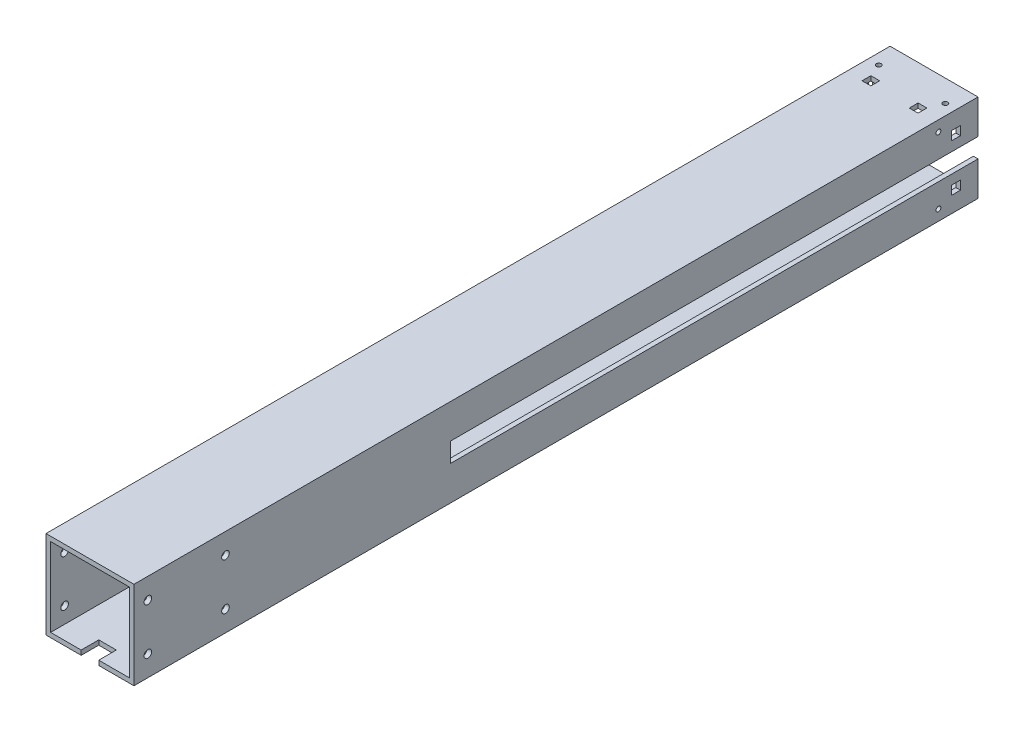
SolidWorks part; units mm, degrees
ref_plane "Front Plane" through (0, 0, 0) normal (1, 0, 0) x (0, 1, 0)
ref_plane "Top Plane" through (0, 0, 0) normal (0, 0, 1) x (0, 1, 0)
ref_plane "Right Plane" through (0, 0, 0) normal (0, 1, 0) x (-1, 0, 0)
sketch "Sketch1" plane through (0, 0, 0) normal (0, 0, 1) x (0, 1, 0)
  line L0 (28.4162, -28.4162) -> (28.4162, 28.4162)
  line L1 (31.75, -31.75) -> (-31.75, -31.75)
  line L2 (31.75, -31.75) -> (31.75, 31.75)
  line L3 (31.75, 31.75) -> (-31.75, 31.75)
  line L4 (-31.75, -31.75) -> (-31.75, 31.75)
  line L5 (31.75, -31.75) -> (-31.75, 31.75) construction
  line L6 (31.75, 31.75) -> (-31.75, -31.75) construction
  line L7 (28.4162, 28.4162) -> (-28.4162, 28.4162)
  line L8 (-28.4162, -28.4162) -> (-28.4162, 28.4162)
  line L9 (28.4162, -28.4162) -> (-28.4162, -28.4162)
  line L11 (6.985, -31.75) -> (-6.985, -31.75)
  line L12 (6.985, -31.75) -> (6.985, -28.4163)
  line L13 (6.985, -28.4163) -> (-6.985, -28.4163)
  line L14 (-6.985, -31.75) -> (-6.985, -28.4163)
  line L15 (6.985, -31.75) -> (-6.985, -28.4163) construction
  line L16 (6.985, -28.4163) -> (-6.985, -31.75) construction
  point P0 (0, 0)
  point P10 (0, -30.0831)
  dimension "D1" = 63.5
  dimension "D3" = 13.97
  dimension "D2" = 56.8325
extrude "Boss-Extrude1" add sketch "Sketch1" along normal blind 609.6 contours L1 L14 L9 L8 L7 L0 L12 L2 L3 L4
sketch "Sketch2" plane through (0, 0, 0) normal (0, 1, 0) x (-1, 0, 0)
  line L0 (-28.4162, 0) -> (28.4162, 0) construction
  line L1 (-28.4162, 0) -> (28.4162, 0) construction
  line L2 (0, 0) -> (0, 609.6) construction
  line L3 (-31.75, 609.6) -> (31.75, 609.6) construction
  line L5 (22.225, 6.35) -> (-22.225, 6.35) construction
  line L6 (22.225, 6.35) -> (22.225, 19.05) construction
  line L7 (22.225, 19.05) -> (-22.225, 19.05) construction
  line L8 (-22.225, 6.35) -> (-22.225, 19.05) construction
  line L9 (22.225, 6.35) -> (-22.225, 19.05) construction
  line L10 (22.225, 19.05) -> (-22.225, 6.35) construction
  circle A3 centre (-22.225, 19.05) radius 1.75 construction
  circle A4 centre (22.225, 19.05) radius 1.75 construction
  circle A5 centre (22.225, 6.35) radius 1.75 construction
  circle A6 centre (-22.225, 6.35) radius 1.75 construction
  circle A7 centre (-24.05, 15.875) radius 1.75
  circle A8 centre (24.05, 15.875) radius 1.75
  point P2 (0, 12.7)
  dimension "D1" = 3.5
  dimension "D2" = 6.35
  dimension "D6" = 15.875
  dimension "D3" = 12.7
  dimension "D4" = 44.45
  dimension "D5" = 24.05
extrude "Cut-Extrude1" cut sketch "Sketch2" against normal blind 254 and the other way blind 254
sketch "Sketch4" plane through (31.75, 0, 0) normal (1, 0, 0) x (0, 1, 0)
  line L0 (-28.4162, 609.6) -> (-28.4162, 0) construction
  line L1 (-28.4162, 609.6) -> (-28.4162, 0) construction
  line L2 (-6.985, 0) -> (-31.75, 0) construction
  line L3 (0, 0) -> (0, 609.6) construction
  line L4 (-6.985, 609.6) -> (-31.75, 609.6) construction
  line L5 (31.75, 0) -> (6.985, 0) construction
  circle A1 centre (-22.225, 25.4) radius 1.75 construction
  circle A3 centre (-12.7, 12.7) radius 1.75 construction
  circle A6 centre (12.7, 12.7) radius 1.75 construction
  circle A7 centre (22.225, 25.4) radius 1.75 construction
  circle A8 centre (24.05, 28.575) radius 1.75
  circle A9 centre (-24.05, 28.575) radius 1.75
  dimension "D1" = 22.225
  dimension "D2" = 3.5
  dimension "D4" = 12.7
  dimension "D6" = 24.05
  dimension "D7" = 3.5
  dimension "D3" = 25.4
  dimension "D5" = 12.7
  dimension "D8" = 28.575
extrude "Cut-Extrude2" cut sketch "Sketch4" against normal blind 254
sketch "Sketch6" plane through (31.75, 0, 0) normal (1, 0, 0) x (0, 1, 0)
  line L0 (31.75, 14.125) -> (31.75, 17.625) construction
  line L5 (31.75, 14.125) -> (31.75, 17.625) construction
  line L6 (0, 0) -> (0, 19.05) construction
  line L7 (15.05, 20.875) -> (19.05, 20.875) construction
  line L8 (15.05, 20.875) -> (15.05, 10.875) construction
  line L9 (15.05, 10.875) -> (19.05, 10.875) construction
  line L10 (19.05, 20.875) -> (19.05, 10.875) construction
  line L11 (13.875, 19.05) -> (20.225, 19.05)
  line L12 (13.875, 19.05) -> (13.875, 12.7)
  line L13 (13.875, 12.7) -> (20.225, 12.7)
  line L14 (20.225, 19.05) -> (20.225, 12.7)
  line L15 (28.4163, 0) -> (-28.4162, 0) construction
  line L16 (-13.875, 12.7) -> (-20.225, 12.7)
  line L17 (-20.225, 19.05) -> (-20.225, 12.7)
  line L18 (-13.875, 19.05) -> (-20.225, 19.05)
  line L19 (-13.875, 19.05) -> (-13.875, 12.7)
  point P3 (0, 0)
  point P7 (31.75, 15.875)
  point P9 (19.05, 15.875)
  point P11 (17.05, 20.875)
  point P12 (20.225, 15.875)
  point P17 (17.05, 19.05)
  dimension "D1" = 10
  dimension "D2" = 4
  dimension "D3" = 19.05
  dimension "D4" = 6.35
  dimension "D5" = 6.35
extrude "Cut-Extrude4" cut sketch "Sketch6" against normal blind 90.678
sketch "Sketch7" plane through (0, 31.75, 0) normal (0, 1, 0) x (-1, 0, 0)
  line L0 (-31.75, 30.325) -> (-31.75, 26.825) construction
  line L1 (-31.75, 30.325) -> (-31.75, 26.825)
  line L2 (0, 0) -> (0, 31.75) construction
  line L3 (-19.05, 33.575) -> (-15.05, 33.575) construction
  line L4 (-19.05, 33.575) -> (-19.05, 23.575) construction
  line L5 (-19.05, 23.575) -> (-15.05, 23.575) construction
  line L6 (-15.05, 33.575) -> (-15.05, 23.575) construction
  line L7 (-20.225, 31.75) -> (-13.875, 31.75)
  line L8 (-20.225, 31.75) -> (-20.225, 25.4)
  line L9 (-20.225, 25.4) -> (-13.875, 25.4)
  line L10 (-13.875, 31.75) -> (-13.875, 25.4)
  line L11 (-31.75, 0) -> (31.75, 0) construction
  line L12 (20.225, 25.4) -> (13.875, 25.4)
  line L13 (13.875, 31.75) -> (13.875, 25.4)
  line L14 (20.225, 31.75) -> (13.875, 31.75)
  line L15 (20.225, 31.75) -> (20.225, 25.4)
  point P6 (-31.75, 28.575)
  point P7 (-19.05, 28.575)
  point P10 (-17.05, 33.575)
  point P14 (-20.225, 28.575)
  point P15 (-17.05, 31.75)
  dimension "D1" = 10
  dimension "D2" = 4
  dimension "D3" = 19.05
  dimension "D4" = 6.35
extrude "Cut-Extrude5" cut sketch "Sketch7" against normal blind 122.174 contours L10 L7 L8 L9 | L15 L14 L13 L12
sketch "Sketch8" plane through (31.75, 0, 0) normal (1, 0, 0) x (0, 1, 0)
  line L0 (31.75, 609.6) -> (31.75, 0) construction
  line L1 (-31.75, 609.6) -> (31.75, 609.6)
  line L2 (-31.75, 609.6) -> (-31.75, 381)
  line L3 (-31.75, 381) -> (31.75, 381)
  line L4 (31.75, 609.6) -> (31.75, 381)
  dimension "D1" = 228.6
extrude "Boss-Extrude2" add sketch "Sketch8" against normal up to surface (3.3338 mm away) up to face at (28.4162, -17.05, 15.875)
sketch "Sketch9" plane through (31.75, 0, 0) normal (1, 0, 0) x (0, 1, 0)
  line L0 (31.75, 609.6) -> (-31.75, 609.6) construction
  line L1 (16.812, 543.48) -> (-16.812, 543.48) construction
  line L2 (16.812, 543.48) -> (16.812, 599.52) construction
  line L3 (16.812, 599.52) -> (-16.812, 599.52) construction
  line L4 (-16.812, 543.48) -> (-16.812, 599.52) construction
  line L5 (16.812, 543.48) -> (-16.812, 599.52) construction
  line L6 (16.812, 599.52) -> (-16.812, 543.48) construction
  circle A0 centre (-16.812, 599.52) radius 2.75
  circle A1 centre (-16.812, 543.48) radius 2.75
  circle A2 centre (16.812, 543.48) radius 2.75
  circle A3 centre (16.812, 599.52) radius 2.75
  point P2 (0, 571.5)
  point P7 (0, 609.6)
  dimension "D1" = 5.5
  dimension "D2" = 33.624
  dimension "D3" = 56.04
  dimension "D4" = 38.1
extrude "Cut-Extrude6" cut sketch "Sketch9" against normal blind 100.584
sketch "Sketch11" plane through (0, -28.4162, 0) normal (0, 1, 0) x (-1, 0, 0)
  line L0 (-31.75, 609.6) -> (31.75, 609.6) construction
  line L1 (6.35, 609.6) -> (-6.35, 609.6)
  line L2 (6.35, 609.6) -> (6.35, 596.9)
  line L3 (6.35, 596.9) -> (-6.35, 596.9)
  line L4 (-6.35, 609.6) -> (-6.35, 596.9)
  point P4 (0, 609.6)
  point P5 (0, 609.6)
  dimension "D1" = 12.7
  dimension "D2" = 12.7
extrude "Cut-Extrude8" cut sketch "Sketch11" against normal blind 31.496
